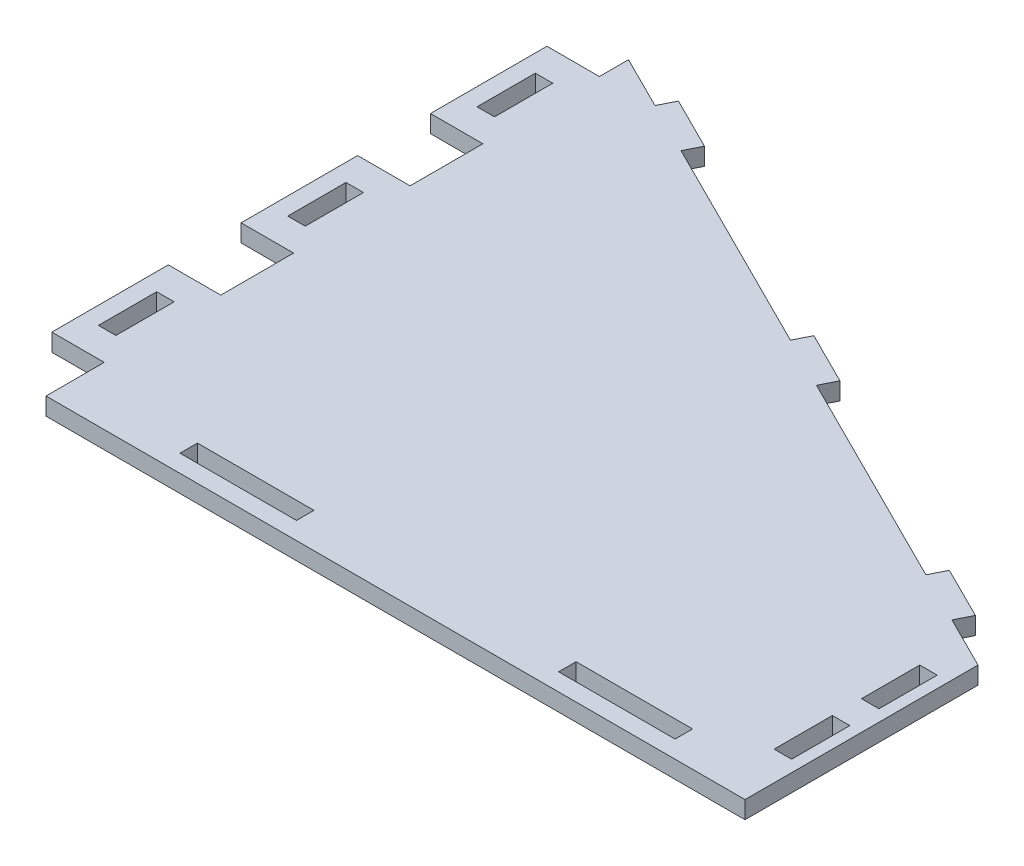
SolidWorks part; units mm, degrees
material "ABS"
ref_plane "Front Plane" through (0, 0, 0) normal (0, 0, 1) x (1, 0, 0)
ref_plane "Top Plane" through (0, 0, 0) normal (0, 1, 0) x (1, 0, 0)
ref_plane "Right Plane" through (0, 0, 0) normal (1, 0, 0) x (0, 0, -1)
sketch "Sketch1" plane through (0, 0, 0) normal (0, 1, 0) x (1, 0, 0)
  line L0 (0, 0) -> (0, 10)
  line L1 (0, 100) -> (9.091, 95.4545)
  line L2 (120, 40) -> (120, 0)
  line L3 (120, 0) -> (0, 0)
  line L4 (9.091, 95.4545) -> (10.4327, 98.1378)
  line L5 (10.4327, 98.1378) -> (19.3769, 93.6656)
  line L6 (19.3769, 93.6656) -> (18.0353, 90.9823)
  line L7 (55.6012, 72.1994) -> (56.9429, 74.8827)
  line L8 (56.9429, 74.8827) -> (65.8872, 70.4105)
  line L9 (65.8872, 70.4105) -> (64.5455, 67.7272)
  line L10 (102.1115, 48.9443) -> (103.4531, 51.6276)
  line L11 (103.4531, 51.6276) -> (112.3974, 47.1554)
  line L12 (112.3974, 47.1554) -> (111.0557, 44.4721)
  line L13 (18.0353, 90.9823) -> (55.6012, 72.1994)
  line L14 (64.5455, 67.7272) -> (102.1115, 48.9443)
  line L15 (111.0557, 44.4721) -> (120, 40)
  line L16 (0, 95) -> (0, 100)
  line L17 (115, 35) -> (118, 35)
  line L18 (115, 35) -> (115, 25)
  line L19 (115, 25) -> (118, 25)
  line L20 (118, 35) -> (118, 25)
  line L21 (115, 20) -> (118, 20)
  line L22 (115, 20) -> (115, 10)
  line L23 (115, 10) -> (118, 10)
  line L24 (118, 20) -> (118, 10)
  line L25 (-9, 95) -> (0, 95)
  line L26 (-9, 95) -> (-9, 75)
  line L27 (-9, 75) -> (0, 75)
  line L29 (-9, 62.5) -> (0, 62.5)
  line L30 (-9, 62.5) -> (-9, 42.5)
  line L31 (-9, 42.5) -> (0, 42.5)
  line L33 (-9, 30) -> (0, 30)
  line L34 (-9, 30) -> (-9, 10)
  line L35 (-9, 10) -> (0, 10)
  line L37 (20, 3) -> (40, 3)
  line L38 (20, 3) -> (20, 6)
  line L39 (20, 6) -> (40, 6)
  line L40 (40, 3) -> (40, 6)
  line L41 (85, 6) -> (105, 6)
  line L42 (85, 6) -> (85, 3)
  line L43 (85, 3) -> (105, 3)
  line L44 (105, 6) -> (105, 3)
  line L45 (0, 62.5) -> (0, 75)
  line L46 (0, 30) -> (0, 42.5)
  line L48 (-6, 90) -> (-3, 90)
  line L49 (-6, 90) -> (-6, 80)
  line L50 (-6, 80) -> (-3, 80)
  line L51 (-3, 90) -> (-3, 80)
  line L52 (-6, 57.5) -> (-3, 57.5)
  line L53 (-6, 57.5) -> (-6, 47.5)
  line L54 (-6, 47.5) -> (-3, 47.5)
  line L55 (-3, 57.5) -> (-3, 47.5)
  line L56 (-6, 25) -> (-3, 25)
  line L57 (-6, 25) -> (-6, 15)
  line L58 (-6, 15) -> (-3, 15)
  line L59 (-3, 25) -> (-3, 15)
  point P13 (65.2163, 69.0689)
  dimension "D1" = 100
  dimension "D2" = 40
  dimension "D3" = 10
  dimension "D4" = 10
  dimension "D5" = 10
  dimension "D6" = 120
  dimension "D7" = 3
  dimension "D8" = 42
  dimension "D9" = 3
  dimension "D10" = 42
  dimension "D11" = 10
  dimension "D12" = 3
  dimension "D13" = 10
  dimension "D14" = 10
  dimension "D15" = 3
  dimension "D16" = 3
  dimension "D17" = 10
  dimension "D18" = 5
  dimension "D19" = 2
  dimension "D20" = 2
  dimension "D21" = 12.5
  dimension "D22" = 9
  dimension "D23" = 3
  dimension "D24" = 20
  dimension "D25" = 20
  dimension "D26" = 20
  dimension "D27" = 10
  dimension "D28" = 10
  dimension "D29" = 12.5
  dimension "D30" = 9
  dimension "D31" = 3
  dimension "D32" = 9
  dimension "D33" = 20
  dimension "D34" = 20
  dimension "D35" = 3
  dimension "D36" = 3
  dimension "D37" = 3
  dimension "D38" = 3
  dimension "D39" = 15
  dimension "D40" = 20
  dimension "D41" = 5
  dimension "D42" = 10
  dimension "D43" = 3
  dimension "D44" = 3
  dimension "D45" = 5
  dimension "D46" = 10
  dimension "D47" = 3
  dimension "D48" = 3
  dimension "D49" = 5
extrude "Boss-Extrude1" add sketch "Sketch1" along normal blind 3
